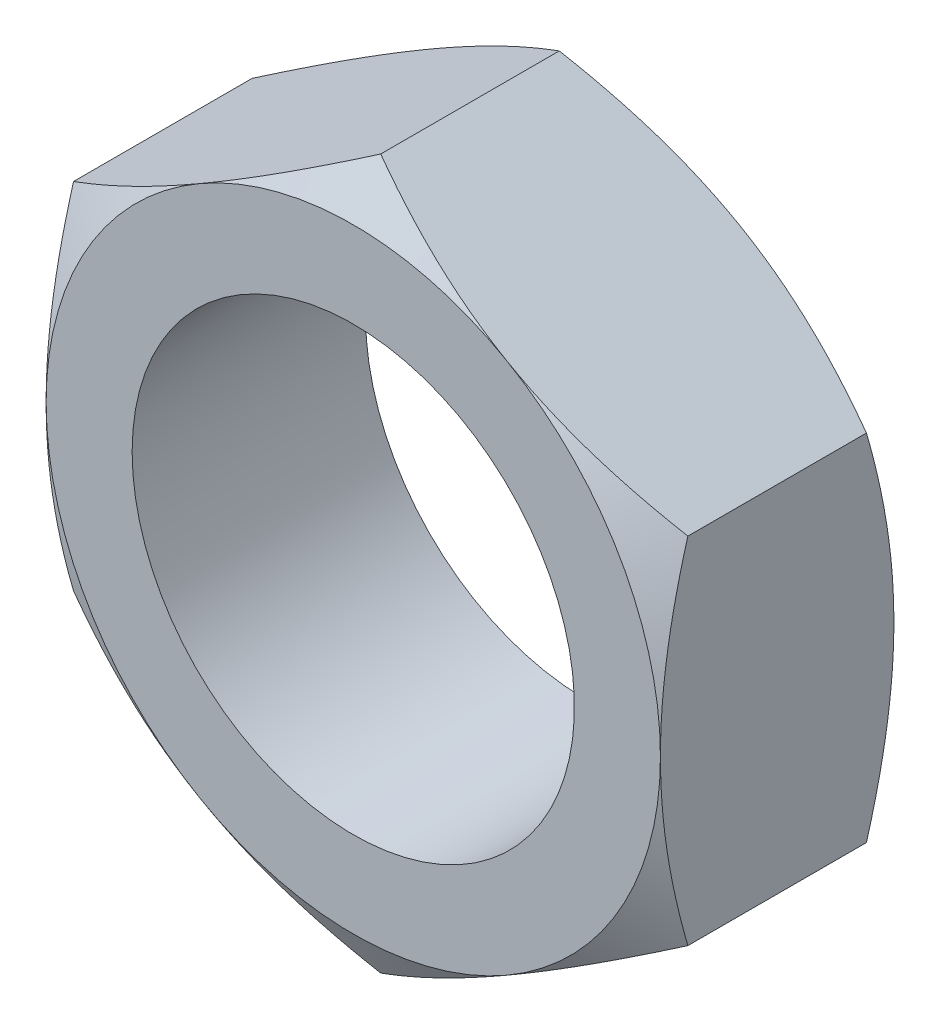
SolidWorks part; units mm, degrees
ref_plane "Front" through (0, 0, 0) normal (0, 0, 1) x (1, 0, 0)
ref_plane "Top" through (0, 0, 0) normal (0, 1, 0) x (1, 0, 0)
ref_plane "Right" through (0, 0, 0) normal (1, 0, 0) x (0, 0, -1)
sketch "Sketch1" plane through (0, 0, 0) normal (0, 0, 1) x (1, 0, 0)
  line L1 (-4.8507, 2.8005) -> (-4.8507, -2.8005)
  line L2 (-4.8507, -2.8005) -> (0, -5.6011)
  line L3 (0, -5.6011) -> (4.8507, -2.8005)
  line L4 (4.8507, -2.8005) -> (4.8507, 2.8005)
  line L5 (4.8507, 2.8005) -> (0, 5.6011)
  line L6 (0, 5.6011) -> (-4.8507, 2.8005)
  circle A0 centre (0, 0) radius 4.8507 construction
  circle A1 centre (0, 0) radius 3.4925 construction
  point P10 (0, 3.4925)
  dimension "hex" = 9.7014
  dimension "dia" = 6.985
extrude "Extrude1" add sketch "Sketch1" along normal mid plane 3.6865
sketch "Sketch4" plane through (0, 0, -1.8433) normal (0, 0, -1) x (-1, 0, 0)
  circle A0 centre (0, 0) radius 3.4925 construction
  circle A1 centre (0, 0) radius 3.4925
sketch "Sketch10" plane through (0, 0, 1.8433) normal (0, 0, 1) x (1, 0, 0)
  circle A0 centre (0, 0) radius 3.4925 construction
  circle A1 centre (0, 0) radius 3.4925
extrude "Cut-Extrude2" cut sketch "Sketch10" against normal through all draft 45
sketch "Sketch11" plane through (0, 0, -1.8433) normal (0, 0, -1) x (-1, 0, 0)
  circle A0 centre (0, 0) radius 3.4925 construction
  circle A1 centre (0, 0) radius 3.4925
extrude "Cut-Extrude3" cut sketch "Sketch11" against normal through all draft 45
sketch "Sketch13" plane through (0, 0, -1.8433) normal (0, 0, -1) x (-1, 0, 0)
  circle A0 centre (0, 0) radius 3.4925 construction
  circle A1 centre (0, 0) radius 3.4925
extrude "Boss-Extrude1" add sketch "Sketch13" against normal up to vertex (3.6865 mm away) separate body up to point (-4.8507, 2.8006, 1.8433)
sketch "Sketch12" plane through (0, 0, 0) normal (1, 0, 0) x (0, 0, -1)
  line L0 (6.2183, 3.4925) -> (1.8433, 3.4925)
  line L1 (6.2183, 3.4925) -> (4.3433, 0.2449)
  line L2 (4.3433, 0.2449) -> (3.7183, 0.2449)
  line L3 (3.7183, 0.2449) -> (1.8433, 3.4925)
  line L4 (4.0308, 0.2449) -> (4.0308, 3.4925) construction
  line L5 (2.7808, 1.8687) -> (5.2808, 1.8687) construction
  dimension "D1" = 60
  dimension "D2" = 0.625
  dimension "D3" = 2.5
combine bodies "Combine1" operation type subtract main body 116 bodies to subtract 117
cosmetic thread "Cosmetic Thread1" parameters "D2"=180
sketch "Sketch7" plane through (0, 0, 1.8433) normal (0, 0, 1) x (1, 0, 0)
  circle A0 centre (0, 0) radius 4.8507 construction
  circle A1 centre (0, 0) radius 4.8507
extrude "Extrude2" cut sketch "Sketch7" against normal blind 25.4 draft 60 flip side to cut
mirror "Mirror2" about plane through (0, 0, 0) normal (0, 0, 1) of "Extrude2"
sketch "Sketch8" plane through (0, 0, 1.8433) normal (0, 0, 1) x (1, 0, 0)
  line L0 (-2.4696, 2.4696) -> (0, 0) construction
  line L1 (0, -1.2955) -> (0, 1.2955) construction
  circle A1 centre (0, 0) radius 3.4925 construction
  point P0 (-2.4696, 2.4696)
  dimension "D1" = 45
sketch "Sketch14" plane through (0, 0, 1.8433) normal (0, 0, 1) x (1, 0, 0)
  line L0 (0, 0) -> (-3.4925, 0) construction
  circle A0 centre (0, 0) radius 3.4925 construction
equation "\"Lower_Mount_piston_rod_radius\"\t=3.4925"
equation "\"dia@Sketch1\"=\"Lower_Mount_piston_rod_radius\"*2"
equation "\"hex@Sketch1\"=\"Lower_Mount_piston_rod_radius\"/0.36"
equation "\"length@Extrude1\"=\"Lower_Mount_piston_rod_radius\"/0.94736842"
equation "\"Upper_Mount_largest_radius\" =26.6"
equation "\"Upper_mount_wall_thickness\" =4"
equation "\"Lower_Mount_piston_rod_length\" =149"
equation "\"Piston_orifice_dia\"=0.30711"
equation "\"Spring_inner_dia\" =80"
equation "\"Spring_wire_dia\" =8"
